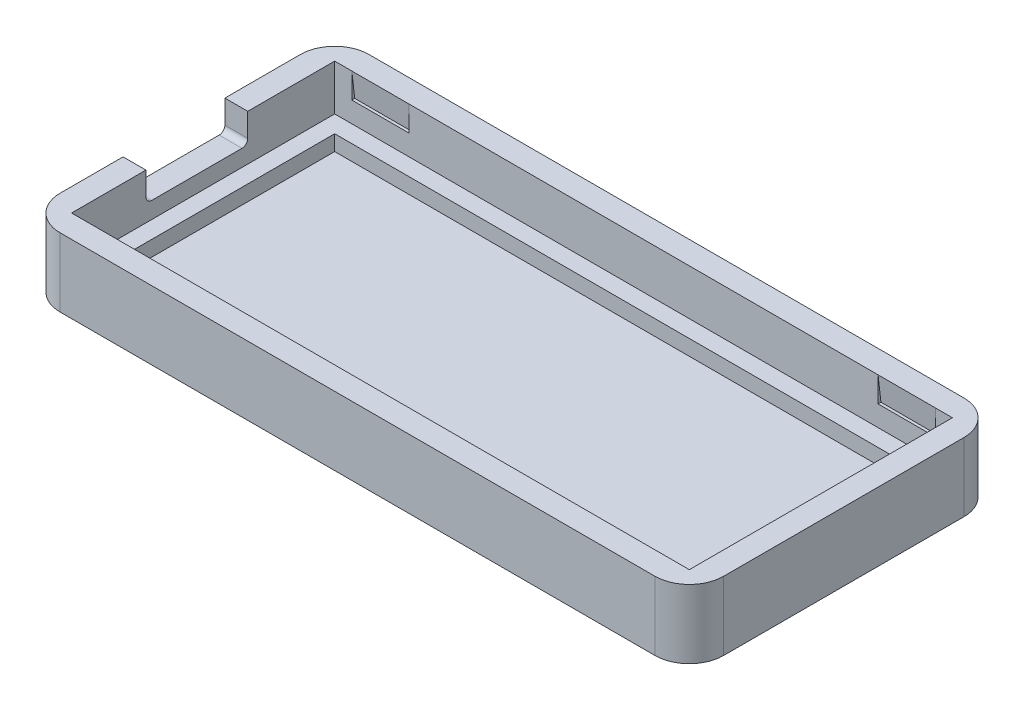
SolidWorks part; units mm, degrees
ref_plane "Front Plane" through (0, 0, 0) normal (0, 0, 1) x (1, 0, 0)
ref_plane "Top Plane" through (0, 0, 0) normal (0, 1, 0) x (1, 0, 0)
ref_plane "Right Plane" through (0, 0, 0) normal (1, 0, 0) x (0, 0, -1)
sketch "Sketch1" plane through (0, 0, 0) normal (0, 1, 0) x (1, 0, 0)
  line L0 (0, 13.5) -> (0, -13.5) construction
  line L1 (-29, 13.5) -> (29, 13.5)
  line L2 (-29, 13.5) -> (-29, -13.5)
  line L3 (-29, -13.5) -> (29, -13.5)
  line L4 (29, 13.5) -> (29, -13.5)
  point P6 (0, 0)
  point P7 (0, 0)
  dimension "D1" = 58
  dimension "D2" = 27
extrude "Boss-Extrude1" add sketch "Sketch1" along normal blind 6
sketch "Sketch2" plane through (0, 6, 0) normal (0, 1, 0) x (1, 0, 0)
  line L0 (0, 11.5) -> (0, -11.5) construction
  line L1 (-27, 11.5) -> (27, 11.5)
  line L2 (-27, 11.5) -> (-27, -11.5)
  line L3 (-27, -11.5) -> (27, -11.5)
  line L4 (27, 11.5) -> (27, -11.5)
  point P6 (0, 0)
  point P7 (0, 0)
  dimension "D1" = 54
  dimension "D2" = 23
extrude "Cut-Extrude1" cut sketch "Sketch2" against normal offset from surface (4 mm away) 2 up to face at (0, 0, 0)
sketch "Sketch3" plane through (-27, 0, 0) normal (1, 0, 0) x (0, 0, -1)
  line L0 (11.5, 6) -> (-11.5, 6) construction
  line L1 (-5, 6) -> (3.9, 6)
  line L2 (-5, 6) -> (-5, 3.45)
  line L3 (-5, 3.45) -> (3.9, 3.45)
  line L4 (3.9, 6) -> (3.9, 3.45)
  line L5 (-11.5, 2) -> (11.5, 2) construction
  line L6 (11.5, 2) -> (11.5, 6) construction
  dimension "D1" = 1.45
  dimension "D2" = 8.9
  dimension "D3" = 7.6
extrude "Cut-Extrude2" cut sketch "Sketch3" against normal through all
fillet "Fillet1" radius 0.5 2 edges at (-28, 3.45, 5) (-28, 3.45, -3.9)
fillet "Fillet2" radius 3 4 edges at (29, 3, -13.5) (29, 3, 13.5) (-29, 3, 13.5) (-29, 3, -13.5)
sketch "Sketch4" plane through (0, 2, 0) normal (0, 1, 0) x (1, 0, 0)
  line L12 (-25.5, 10) -> (-25.5, -10)
  line L13 (-25.5, -10) -> (25.5, -10)
  line L14 (25.5, -10) -> (25.5, 10)
  line L15 (25.5, 10) -> (-25.5, 10)
  line L16 (-25.5, 10) -> (-25.5, -10)
  line L17 (-25.5, -10) -> (25.5, -10)
  line L18 (25.5, -10) -> (25.5, 10)
  line L19 (25.5, 10) -> (-25.5, 10)
  dimension "D1" = 1.5
extrude "Cut-Extrude3" cut sketch "Sketch4" against normal blind 1.35
ref_plane "Plane1" through (25.5, 0, 0) normal (-1, 0, 0) x (0, 0, 1)
sketch "Sketch6" plane through (25.5, 0, 0) normal (-1, 0, 0) x (0, 0, 1)
  line L0 (-11.5, 2) -> (-11.5, 6) construction
  line L1 (-11.5, 2) -> (-11.5, 6)
  line L2 (-11.5, 6) -> (-11.75, 3.8)
  line L3 (-11.75, 3.8) -> (-11.5, 3.8)
  line L4 (11.5, 2) -> (11.5, 6) construction
  line L5 (11.5, 2) -> (11.5, 6)
  line L6 (11.5, 6) -> (11.75, 3.8)
  line L7 (11.75, 3.8) -> (11.5, 3.8)
  dimension "D1" = 0.25
  dimension "D2" = 2.2
extrude "Cut-Extrude5" cut sketch "Sketch6" along normal blind 5 contours L2 L3 L1 | L7 L6 L5
mirror "Mirror1" about plane through (0, 0, 0) normal (1, 0, 0) of "Cut-Extrude5"
